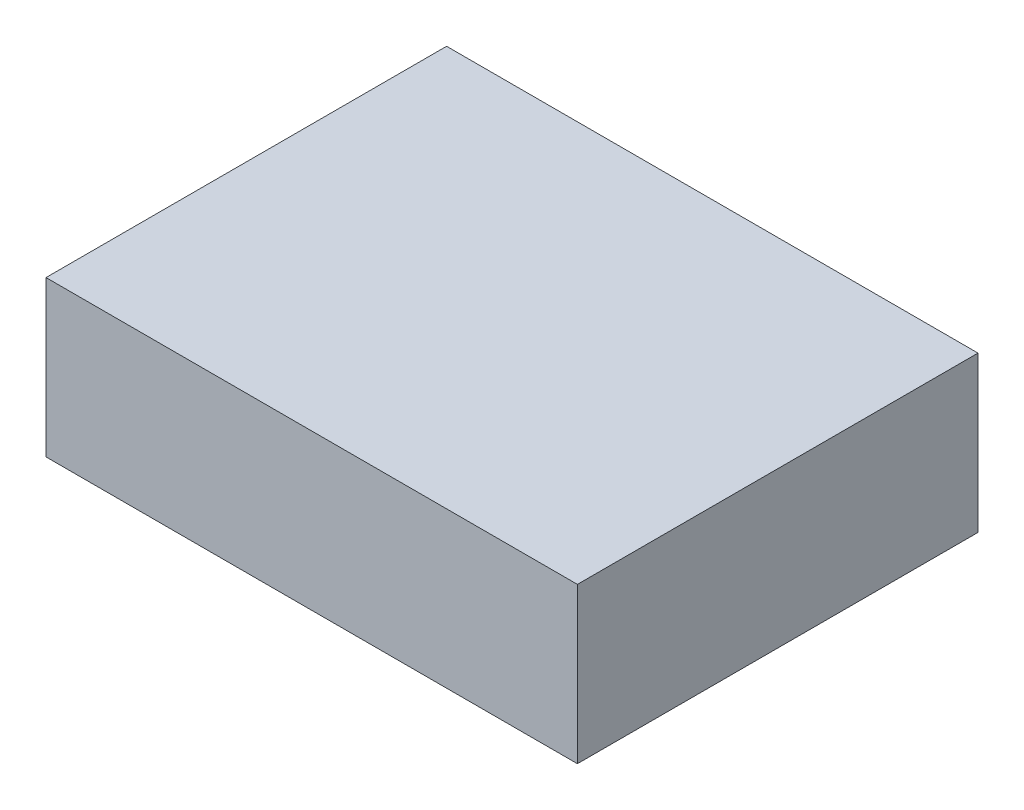
SolidWorks part; units mm, degrees
ref_plane "Front Plane" through (0, 0, 0) normal (0, 0, 1) x (1, 0, 0)
ref_plane "Top Plane" through (0, 0, 0) normal (0, 1, 0) x (1, 0, 0)
ref_plane "Right Plane" through (0, 0, 0) normal (1, 0, 0) x (0, 0, -1)
sketch "Sketch2" plane through (0, 0, 0) normal (0, 1, 0) x (1, 0, 0)
  line L0 (-65, 49) -> (-65, -49)
  line L1 (-65, -49) -> (65, -49)
  line L2 (65, -49) -> (65, 49)
  line L3 (65, 49) -> (-65, 49)
  point P2 (-65, 0)
  point P5 (0, 49)
  dimension "D1" = 130
  dimension "D2" = 98
extrude "Boss-Extrude1" add sketch "Sketch2" along normal blind 38
